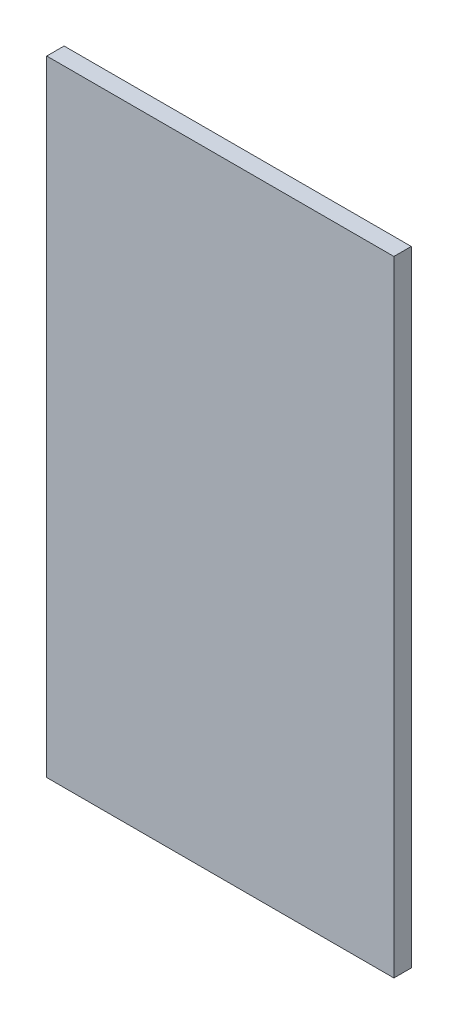
SolidWorks part; units mm, degrees
material "Thornel Mat VMA"
ref_plane "Front Plane" through (0, 0, 0) normal (0, 0, 1) x (1, 0, 0)
ref_plane "Top Plane" through (0, 0, 0) normal (0, 1, 0) x (1, 0, 0)
ref_plane "Right Plane" through (0, 0, 0) normal (1, 0, 0) x (0, 0, -1)
sketch "Sketch1" plane through (0, 0, 0) normal (0, 0, 1) x (1, 0, 0)
  line L1 (-50, -90) -> (50, -90)
  line L2 (-50, -90) -> (-50, 90)
  line L3 (-50, 90) -> (50, 90)
  line L4 (50, -90) -> (50, 90)
  line L5 (-50, -90) -> (50, 90) construction
  line L6 (-50, 90) -> (50, -90) construction
  point P0 (0, 0)
  dimension "D1" = 180
  dimension "D2" = 100
extrude "Boss-Extrude1" add sketch "Sketch1" along normal blind 5
